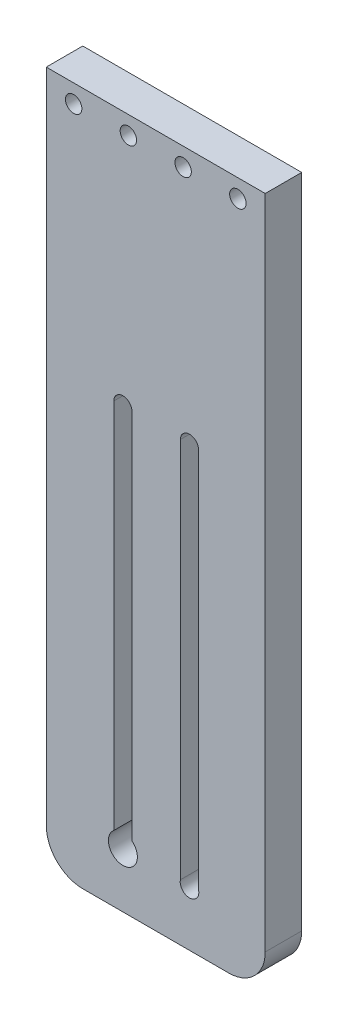
SolidWorks part; units mm, degrees
material "Сплав 2024"
ref_plane "Спереди" through (0, 0, 0) normal (0, 0, 1) x (1, 0, 0)
ref_plane "Сверху" through (0, 0, 0) normal (0, 1, 0) x (1, 0, 0)
ref_plane "Справа" through (0, 0, 0) normal (1, 0, 0) x (0, 0, -1)
sketch "Эскиз1" plane through (0, 0, 0) normal (0, 0, 1) x (1, 0, 0)
  line L0 (31.6276, -80) -> (0, -80) construction
  line L1 (0, 0) -> (60, 0)
  line L2 (0, 0) -> (0, -190)
  line L3 (0, -190) -> (60, -190)
  line L4 (60, 0) -> (60, -60)
  line L5 (30, 0) -> (30, -190) construction
  line L6 (0, -60) -> (-30, -70.9191) construction
  line L7 (-30, -70.9191) -> (-30, -139.0809) construction
  line L8 (-30, -139.0809) -> (0, -150) construction
  line L9 (0, 0) -> (0, -60) construction
  line L10 (0, -150) -> (0, -190) construction
  line L11 (60, -60) -> (60, -150)
  line L15 (60, -150) -> (60, -190)
  line L16 (90, -139.0809) -> (60, -150) construction
  line L17 (90, -70.9191) -> (90, -139.0809) construction
  line L18 (60, -60) -> (90, -70.9191) construction
  dimension "D1" = 40
  dimension "D2" = 190
  dimension "D3" = 80
  dimension "D4" = 60
  dimension "D5" = 60
  dimension "D6" = 90
  dimension "D7" = 110
  dimension "D8" = 110
extrude "Бобышка-Вытянуть1" add sketch "Эскиз1" along normal blind 10
sketch "Эскиз4" plane through (0, 0, 0) normal (0, 0, -1) x (-1, 0, 0)
  line L0 (-30, 0) -> (-30, -190) construction
  line L1 (-40.1, -15) -> (-19.9, -15)
  line L2 (-40.1, -15) -> (-40.1, -64.75)
  line L3 (-40.1, -64.75) -> (-19.9, -64.75)
  line L4 (-19.9, -15) -> (-19.9, -64.75)
  line L5 (-40.1, -15) -> (-19.9, -64.75) construction
  line L6 (-40.1, -64.75) -> (-19.9, -15) construction
  line L7 (0, 0) -> (-60, 0) construction
  point P0 (-30, -39.875)
  dimension "D1" = 20.2
  dimension "D2" = 15
  dimension "D4" = 49.75
sketch "Эскиз6" [suppressed] plane through (0, 0, 0) normal (0, 0, -1) x (-1, 0, 0)
  line L1 (-60, 0) -> (-60, -60) construction
  line L2 (-57, -15) -> (-43.1, -15)
  line L3 (-57, -15) -> (-57, -59.1006)
  line L4 (-57, -59.1006) -> (-43.1, -59.1006)
  line L5 (-43.1, -15) -> (-43.1, -59.1006)
  line L6 (-57, -15) -> (-43.1, -59.1006) construction
  line L8 (-57, -59.1006) -> (-43.1, -15) construction
  line L9 (-40.1, -15) -> (-40.1, -62.1006) construction
  line L11 (-40.1, -62.1006) -> (-57, -62.1006) construction
  line L12 (-19.9, -15) -> (-40.1, -15) construction
  line L13 (-30, 0) -> (-30, -7.5553) construction
  line L14 (-30, 0) -> (-30, -180) construction
  line L15 (-3, -59.1006) -> (-16.9, -15) construction
  line L16 (-3, -15) -> (-16.9, -59.1006) construction
  line L17 (-16.9, -15) -> (-16.9, -59.1006)
  line L18 (-3, -59.1006) -> (-16.9, -59.1006)
  line L19 (-3, -15) -> (-3, -59.1006)
  line L20 (-3, -15) -> (-16.9, -15)
  point P0 (-50.05, -37.0503)
  point P7 (-6.15, -152.5)
  point P8 (-40.1, -38.5503)
  point P13 (-15.69, -152.5)
  point P14 (-25.23, -152.5)
  point P15 (-34.77, -152.5)
  point P16 (-44.31, -152.5)
  point P17 (-48.55, -62.1006)
  point P28 (-9.95, -37.0503)
  dimension "D1" = 3
  dimension "D2" = 3
  dimension "D3" = 3
hole_wizard "Цековка для винта с внутренним шестигранником M4" positions "Эскиз7" profile "Эскиз8" counterbore size "M4" standard "Ansi Metric"
sketch "Эскиз7" plane through (-14.8427, -41.6551, 0) normal (0, 0, -1) x (-1, 0, 0)
  point P0 (-67.3427, 36.6551)
  point P3 (-52.3427, 36.6551)
  point P6 (-37.3427, 36.6551)
  point P9 (-22.3427, 36.6551)
sketch "Эскиз8" plane through (52.5, -5, 0) normal (1, 0, 0) x (0, 1, 0)
  line L0 (0, 0) -> (0, 11.3509)
  line L1 (0, 11.3509) -> (2.25, 9.999)
  line L2 (2.25, 9.999) -> (2.25, 4)
  line L3 (2.25, 4) -> (4, 4)
  line L4 (4, 4) -> (4, 0)
  line L5 (4, 0) -> (0, 0)
  line L6 (0, 11.3509) -> (-2.25, 9.999) construction
  line L7 (0, -6.35) -> (0, 107.95) construction
  dimension "Диаметр отверстия" = 4.5
  dimension "Глубина отверстия" = 9.999
  dimension "Диаметр цековки" = 8
  dimension "Глубина цековки" = 4
  dimension "Угол заточки сверла" = 118
sketch "Эскиз9" plane through (0, 0, 10) normal (0, 0, -1) x (-1, 0, 0)
  line L0 (-39.25, -190) -> (-39.25, 0) construction
  line L1 (0, -190) -> (-60, -190) construction
  line L2 (-60, 0) -> (0, 0) construction
  line L3 (-21, -190) -> (-21, 0) construction
  line L4 (0, 0) -> (0, -190) construction
  line L5 (-60, -175) -> (0, -175) construction
  line L6 (-60, -190) -> (-60, 0) construction
  dimension "D1" = 18.25
  dimension "D2" = 21
  dimension "D3" = 15
hole_wizard "Отверстие обработанное метчиком 1/4-201" positions "Трехмерный эскиз1" profile "Эскиз10" tap size "1/4-20" standard "Ansi Inch" end condition through all
sketch3d "Трехмерный эскиз1"
  line L0 (60, -175, 10) -> (0, -175, 10) construction
  line L1 (39.25, -190, 10) -> (39.25, 0, 10) construction
  point P0 (39.25, -175, 10)
sketch "Эскиз10" plane through (39.25, -175, 10) normal (1, 0, 0) x (0, -1, 0)
  line L0 (0, 0) -> (0, 10)
  line L1 (0, 10) -> (2.5527, 10)
  line L2 (2.5527, 10) -> (2.5527, 0)
  line L5 (2.5527, 0) -> (0, 0)
  line L11 (0, -6.35) -> (0, 107.95) construction
  dimension "Диаметр резьбы" = 5.1054
  dimension "Глубина проходного сверла" = 10
hole_wizard "Отверстие обработанное метчиком 3/8-161" positions "Трехмерный эскиз2" profile "Эскиз11" tap size "3/8-16" standard "Ansi Inch" end condition through all
sketch3d "Трехмерный эскиз2"
  line L0 (21, -190, 10) -> (21, 0, 10) construction
  line L1 (60, -175, 10) -> (0, -175, 10) construction
  point P0 (21, -175, 10)
sketch "Эскиз11" plane through (21, -175, 10) normal (1, 0, 0) x (0, -1, 0)
  line L0 (0, 0) -> (0, 10)
  line L1 (0, 10) -> (3.9687, 10)
  line L2 (3.9687, 10) -> (3.9687, 0)
  line L5 (3.9687, 0) -> (0, 0)
  line L11 (0, -6.35) -> (0, 107.95) construction
  dimension "Диаметр резьбы" = 7.9375
  dimension "Глубина проходного сверла" = 10
sketch "Эскиз12" plane through (0, 0, 10) normal (0, 0, 1) x (1, 0, 0)
  line L0 (39.25, -175) -> (39.25, -70) construction
  line L1 (39.25, -190) -> (39.25, 0) construction
  line L2 (36.75, -175) -> (36.75, -70)
  line L3 (41.75, -175) -> (41.75, -70)
  line L4 (21, -175) -> (21, -70) construction
  line L5 (21, -190) -> (21, 0) construction
  line L6 (18.5, -175) -> (18.5, -70)
  line L7 (23.5, -175) -> (23.5, -70)
  line L8 (31.75, -175) -> (31.75, -70) construction
  line L9 (46.75, -175) -> (46.75, -70) construction
  line L10 (13.5, -175) -> (13.5, -70) construction
  line L11 (28.5, -175) -> (28.5, -70) construction
  arc A0 (36.75, -175) -> (41.75, -175) centre (39.25, -175) ccw
  arc A1 (41.75, -70) -> (36.75, -70) centre (39.25, -70) ccw
  arc A2 (18.5, -175) -> (23.5, -175) centre (21, -175) ccw
  arc A3 (23.5, -70) -> (18.5, -70) centre (21, -70) ccw
  arc A4 (46.75, -70) -> (31.75, -70) centre (39.25, -70) ccw construction
  arc A5 (31.75, -175) -> (46.75, -175) centre (39.25, -175) ccw construction
  arc A6 (28.5, -70) -> (13.5, -70) centre (21, -70) ccw construction
  arc A7 (13.5, -175) -> (28.5, -175) centre (21, -175) ccw construction
  point P5 (39.25, -122.5)
  point P10 (21, -122.5)
  dimension "D1" = 2.5
  dimension "D2" = 105
  dimension "D3" = 5
extrude "Вырез-Вытянуть1" cut sketch "Эскиз12" against normal through all
fillet "Скругление1" radius 10 2 edges at (0, -190, 5) (60, -190, 5)
sketch "Эскиз14" plane through (0, 0, 0) normal (0, 0, -1) x (-1, 0, 0)
  line L0 (-30, 0) -> (-30, 4.7493) construction
  line L1 (-40.1, -15) -> (-19.9, -15)
  line L2 (-40.1, -15) -> (-40.1, -55)
  line L3 (-40.1, -55) -> (-19.9, -55)
  line L4 (-19.9, -15) -> (-19.9, -55)
  line L5 (-40.1, -15) -> (-19.9, -55) construction
  line L6 (-40.1, -55) -> (-19.9, -15) construction
  line L7 (-60, 0) -> (0, 0) construction
  point P0 (-30, -35)
  dimension "D1" = 20.2
  dimension "D2" = 40
  dimension "D3" = 15
sketch "Эскиз15" plane through (0, 0, 0) normal (0, 0, -1) x (-1, 0, 0)
  circle A0 centre (-40.1, -55) radius 2
  circle A1 centre (-19.9, -55) radius 2
  dimension "D1" = 4
  dimension "D2" = 4
extrude "Вырез-Вытянуть2" cut sketch "Эскиз14" against normal blind 7
extrude "Вырез-Вытянуть3" cut sketch "Эскиз15" against normal blind 7
fillet "Скругление2" radius 4 6 edges at (40.1, -53, 3.5) (38.1, -55, 3.5) (21.9, -55, 3.5) (19.9, -53, 3.5) (19.9, -15, 3.5) (40.1, -15, 3.5)
sketch "Эскиз16" plane through (0, 0, 0) normal (0, 0, -1) x (-1, 0, 0)
  line L0 (-43.6355, -58.5355) -> (-50, -52.1711)
  line L1 (-21, -190) -> (-21, 0) construction
  line L2 (-43.1, -15) -> (-57, -15)
  line L3 (-60, -180) -> (-60, 0) construction
  line L4 (-30, 0) -> (-30, -4.3316) construction
  line L5 (-50, -52.1711) -> (-50, -180)
  line L6 (-38.6183, -15) -> (-63.5936, -15) construction
  line L7 (-53, -44.9284) -> (-44.7546, -53.1738)
  line L8 (-60, 0) -> (0, 0) construction
  line L9 (5.8649, -180) -> (-62.5976, -180) construction
  line L10 (-10, -190) -> (-50, -190) construction
  line L11 (-43, -180) -> (-43, -190) construction
  line L12 (-17, -180) -> (-17, -190) construction
  line L13 (-40.1, -15) -> (-19.9, -15) construction
  line L14 (-65.8649, -180) -> (2.5976, -180) construction
  line L15 (-21.3817, -15) -> (3.5936, -15) construction
  line L16 (-16.9, -15) -> (-16.9, -50.5279)
  line L17 (-7, -44.9284) -> (-7, -180)
  line L18 (-17, -187) -> (-21, -187)
  line L19 (-3, -15) -> (-3, -180)
  line L20 (-7, -44.9284) -> (-15.2454, -53.1738)
  line L21 (-10, -52.1711) -> (-10, -180)
  line L22 (-16.9, -15) -> (-3, -15)
  line L23 (-16.3645, -58.5355) -> (-10, -52.1711)
  line L25 (-23.9, -15) -> (-36.1, -15) construction
  line L203 (-57, -15) -> (-57, -180)
  line L204 (-43, -187) -> (-21, -187)
  line L206 (-53, -44.9284) -> (-53, -180)
  line L210 (-16.9, -50.5279) -> (-16.9, -19)
  line L211 (-35.6279, -58) -> (-24.3721, -58)
  line L212 (-43.1, -19) -> (-43.1, -50.5279)
  line L213 (-23.9, -12) -> (-36.1, -12)
  line L215 (-35.6279, -58) -> (-24.3721, -58)
  line L216 (-43.1, -15) -> (-43.1, -50.5279)
  arc A0 (-57, -180) -> (-53, -180) centre (-55, -180) ccw
  arc A1 (-43.4333, -51.2732) -> (-44.741, -53.1396) centre (-40.1, -55) ccw
  arc A2 (-50, -180) -> (-43, -187) centre (-43, -180) ccw
  arc A3 (-43.6355, -58.5355) -> (-36.3732, -58.3333) centre (-40.1, -55) ccw
  arc A4 (-16.5667, -51.2732) -> (-23.6268, -58.3333) centre (-19.9, -55) cw construction
  arc A5 (-16.5667, -51.2732) -> (-16.9, -50.5279) centre (-15.9, -50.5279) cw
  arc A6 (-24.3721, -58) -> (-23.6268, -58.3333) centre (-24.3721, -59) cw
  arc A7 (-16.3645, -58.5355) -> (-23.6268, -58.3333) centre (-19.9, -55) cw
  arc A8 (-10, -180) -> (-17, -187) centre (-17, -180) cw
  arc A9 (-16.5667, -51.2732) -> (-15.259, -53.1396) centre (-19.9, -55) cw
  arc A10 (-3, -180) -> (-7, -180) centre (-5, -180) cw
  arc A239 (-16.9, -19) -> (-23.9, -12) centre (-23.9, -19) ccw
  arc A240 (-16.9, -50.5279) -> (-16.5667, -51.2732) centre (-15.9, -50.5279) ccw
  arc A241 (-23.6268, -58.3333) -> (-16.5667, -51.2732) centre (-19.9, -55) ccw
  arc A242 (-23.6268, -58.3333) -> (-24.3721, -58) centre (-24.3721, -59) ccw
  arc A243 (-35.6279, -58) -> (-36.3732, -58.3333) centre (-35.6279, -59) ccw
  arc A244 (-43.4333, -51.2732) -> (-36.3732, -58.3333) centre (-40.1, -55) ccw
  arc A245 (-43.4333, -51.2732) -> (-43.1, -50.5279) centre (-44.1, -50.5279) ccw
  arc A246 (-36.1, -12) -> (-43.1, -19) centre (-36.1, -19) ccw
  arc A251 (-35.6279, -58) -> (-36.3732, -58.3333) centre (-35.6279, -59) ccw
  arc A252 (-43.4333, -51.2732) -> (-36.3732, -58.3333) centre (-40.1, -55) ccw construction
  arc A253 (-43.4333, -51.2732) -> (-43.1, -50.5279) centre (-44.1, -50.5279) ccw
  point P52 (-30, -190)
  dimension "D11" = 7
  dimension "D12" = 2
  dimension "D1" = 3
  dimension "D3" = 4
  dimension "D4" = 3
  dimension "D5" = 38.1396
  dimension "D8" = 10
  dimension "D9" = 3
  dimension "D14" = 3
  dimension "D2" = 3
extrude "Вырез-Вытянуть4" [suppressed] cut sketch "Эскиз16" against normal blind 7 contours L21 A8 L18 L204 A2 L5 L0 A3 A251 L215 A6 A7 L23
equation "\"D6@Эскиз1\"=\"D5@Эскиз1\"+30"
equation "\"D2@Эскиз15\" = \"D1@Эскиз15\""
